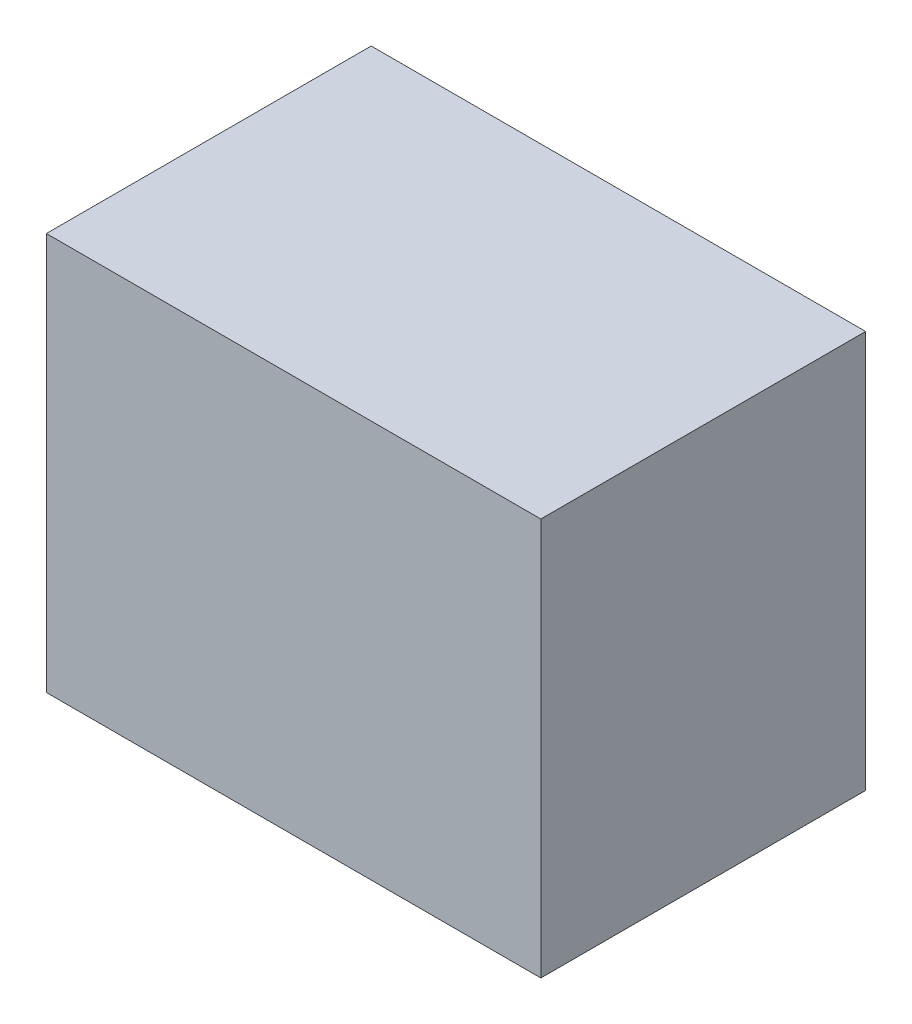
SolidWorks part; units mm, degrees
ref_plane "Front Plane" through (0, 0, 0) normal (0, 0, 1) x (1, 0, 0)
ref_plane "Top Plane" through (0, 0, 0) normal (0, 1, 0) x (1, 0, 0)
ref_plane "Right Plane" through (0, 0, 0) normal (1, 0, 0) x (0, 0, -1)
sketch "Sketch1" plane through (0, 0, 0) normal (0, 1, 0) x (1, 0, 0)
  line L1 (0, 0) -> (259.08, 0)
  line L2 (0, 0) -> (0, 170.18)
  line L3 (0, 170.18) -> (259.08, 170.18)
  line L4 (259.08, 0) -> (259.08, 170.18)
  dimension "D1" = 259.08
  dimension "D2" = 170.18
extrude "Boss-Extrude1" add sketch "Sketch1" along normal blind 208.28
